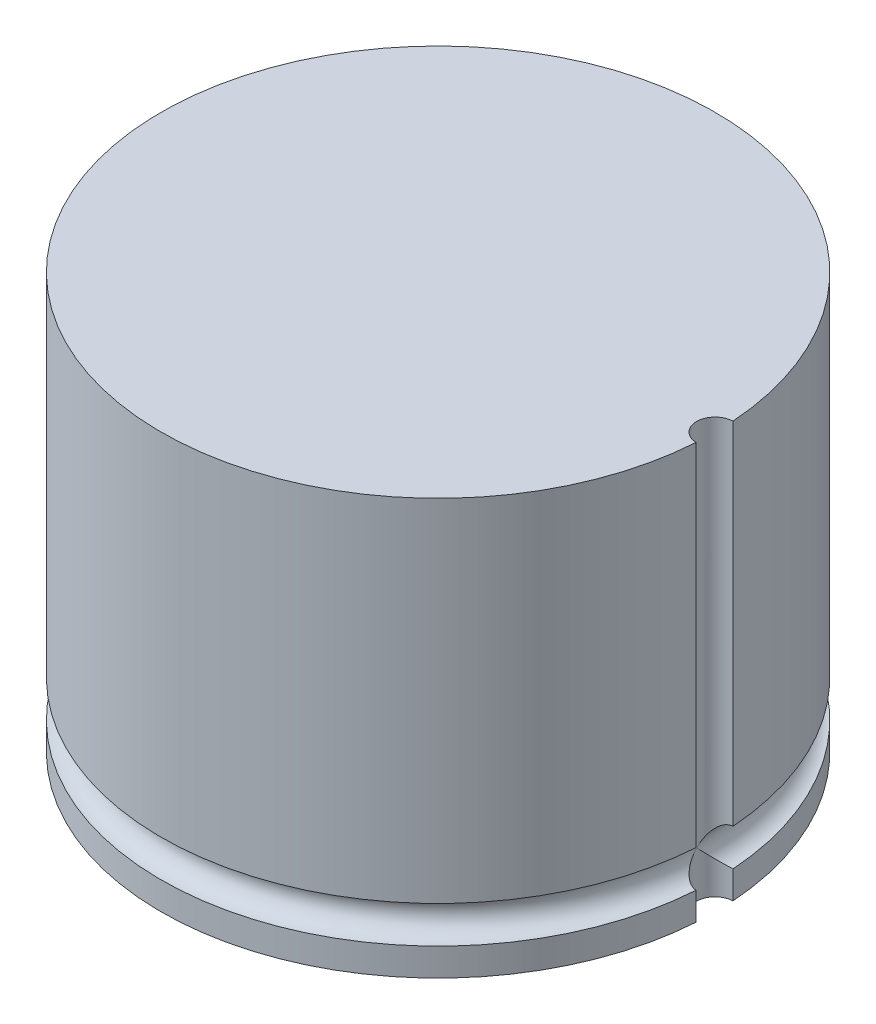
SolidWorks part; units mm, degrees
ref_plane "Спереди" through (0, 0, 0) normal (0, 0, 1) x (1, 0, 0)
ref_plane "Сверху" through (0, 0, 0) normal (0, 1, 0) x (1, 0, 0)
ref_plane "Справа" through (0, 0, 0) normal (1, 0, 0) x (0, 0, -1)
sketch "Эскиз2" plane through (0, 0, 0) normal (0, 1, 0) x (1, 0, 0)
  circle A0 centre (0, 0) radius 30
extrude "Бобышка-Вытянуть1" add sketch "Эскиз2" along normal blind 45
sketch "Эскиз3" plane through (0, 0, 0) normal (1, 0, 0) x (0, 0, -1)
  line L0 (-30, 45) -> (-30, 0) construction
  line L1 (0, 0) -> (0, 56.1845) construction
  circle A0 centre (-30, 5) radius 2
revolve "Вырез-Повернуть1" cut sketch "Эскиз3" angle 360 about L1
sketch "Эскиз4" plane through (0, 0, 0) normal (0, -1, 0) x (1, 0, 0)
  circle A0 centre (-5, 0) radius 1
  circle A1 centre (5, 0) radius 1
  dimension "D1" = 5
  dimension "D3" = 2
  dimension "D4" = 2
  dimension "D2" = 5
extrude "Бобышка-Вытянуть2" add sketch "Эскиз4" along normal blind 6 contours A1 | A0
sketch "Эскиз5" plane through (0, 0, 0) normal (0, -1, 0) x (1, 0, 0)
  circle A0 centre (30, 0) radius 2
  circle A1 centre (0, 0) radius 30 construction
extrude "Вырез-Вытянуть1" cut sketch "Эскиз5" against normal blind 45
